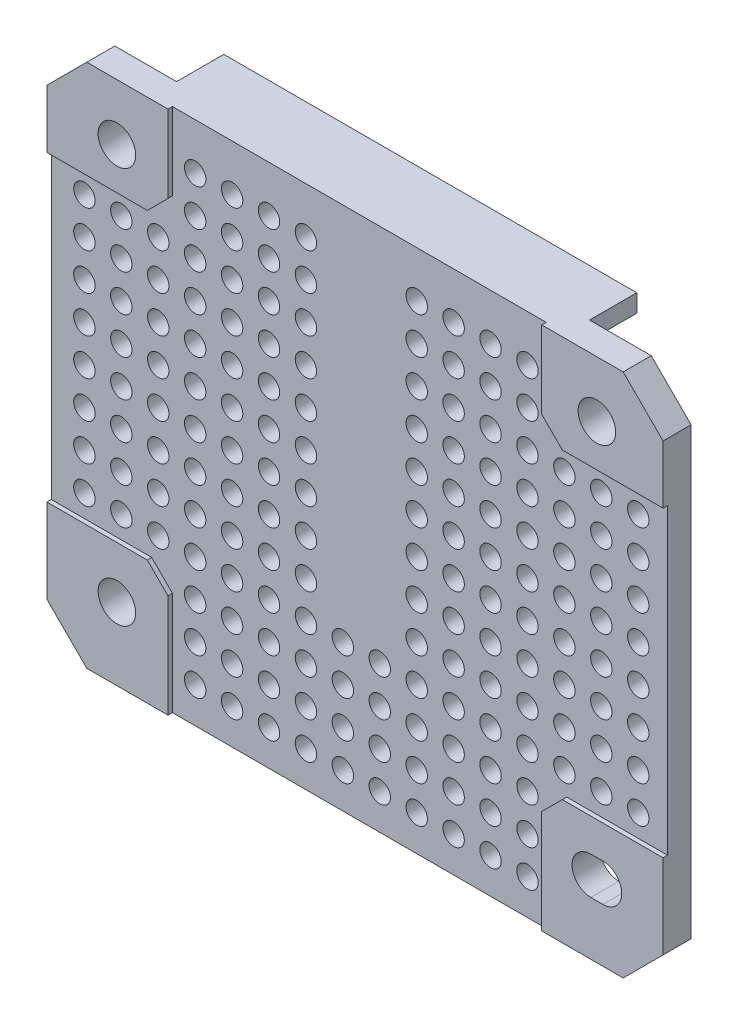
SolidWorks part; units mm, degrees
ref_plane "Front Plane" through (0, 0, 0) normal (0, 0, 1) x (1, 0, 0)
ref_plane "Top Plane" through (0, 0, 0) normal (0, 1, 0) x (1, 0, 0)
ref_plane "Right Plane" through (0, 0, 0) normal (1, 0, 0) x (0, 0, -1)
sketch "Sketch1" plane through (0, 0, 0) normal (0, 0, 1) x (1, 0, 0)
  line L0 (0, 41.7068) -> (3.429, 45.1358)
  line L1 (3.429, 0) -> (49.5554, 0)
  line L2 (0, 3.429) -> (0, 41.7068)
  line L3 (3.429, 45.1358) -> (49.5554, 45.1358)
  line L4 (52.9844, 3.429) -> (52.9844, 41.7068)
  line L5 (49.5554, 45.1358) -> (52.9844, 41.7068)
  line L6 (49.5554, 0) -> (52.9844, 3.429)
  line L7 (0, 3.429) -> (3.429, 0)
  point P0 (0, 0)
  point P1 (52.9844, 45.1358)
  point P2 (0, 45.1358)
  point P3 (52.9844, 0)
  dimension "D1" = 3.429
  dimension "D2" = 45
  dimension "D3" = 3.429
  dimension "D4" = 45
  dimension "D5" = 3.429
  dimension "D6" = 45
  dimension "D7" = 3.429
  dimension "D8" = 45
  dimension "D9" = 52.9844
  dimension "D10" = 45.1358
extrude "Boss-Extrude1" add sketch "Sketch1" along normal blind 2.032
sketch "Sketch2" plane through (0, 0, 2.032) normal (0, 0, 1) x (1, 0, 0)
  line L0 (3.429, 45.1358) -> (0, 41.7068)
  line L1 (0, 41.7068) -> (0, 36.703)
  line L2 (0, 41.7068) -> (0, 3.429) construction
  line L3 (0, 36.703) -> (8.636, 36.703)
  line L4 (10.414, 38.481) -> (10.414, 45.1358)
  line L5 (49.5554, 45.1358) -> (3.429, 45.1358) construction
  line L6 (42.545, 45.1358) -> (42.545, 38.481)
  line L7 (44.323, 36.703) -> (52.9844, 36.703)
  line L8 (52.9844, 3.429) -> (52.9844, 41.7068) construction
  line L9 (42.545, 45.1358) -> (49.5554, 45.1358)
  line L10 (49.5554, 45.1358) -> (52.9844, 41.7068)
  line L11 (52.9844, 41.7068) -> (52.9844, 36.703)
  line L12 (3.429, 45.1358) -> (10.414, 45.1358)
  line L13 (0, 10.668) -> (8.636, 10.668)
  line L14 (10.414, 8.89) -> (10.414, 0)
  line L15 (3.429, 0) -> (49.5554, 0) construction
  line L16 (10.414, 0) -> (3.429, 0)
  line L17 (3.429, 0) -> (0, 3.429)
  line L18 (0, 3.429) -> (0, 10.668)
  line L19 (52.9844, 10.668) -> (44.323, 10.668)
  line L20 (42.545, 8.89) -> (42.545, 0)
  line L21 (42.545, 0) -> (49.5554, 0)
  line L22 (49.5554, 0) -> (52.9844, 3.429)
  line L23 (52.9844, 3.429) -> (52.9844, 10.668)
  line L24 (8.636, 36.703) -> (10.414, 38.481)
  line L25 (42.545, 38.481) -> (44.323, 36.703)
  line L26 (44.323, 10.668) -> (42.545, 8.89)
  line L27 (8.636, 10.668) -> (10.414, 8.89)
  point P8 (10.414, 36.703)
  point P12 (42.545, 36.703)
  point P21 (10.414, 10.668)
  point P30 (42.545, 10.668)
  dimension "D1" = 1.778
  dimension "D2" = 45
  dimension "D3" = 1.778
  dimension "D4" = 45
  dimension "D5" = 1.778
  dimension "D6" = 45
  dimension "D7" = 1.778
  dimension "D8" = 45
  dimension "D9" = 10.668
  dimension "D10" = 10.414
  dimension "D11" = 32.131
  dimension "D12" = 26.035
extrude "Boss-Extrude2" add sketch "Sketch2" along direction (0, 0, -1) on the side of the normal blind 0.381
sketch "Sketch3" plane through (0, 0, 0) normal (0, 0, -1) x (-1, 0, 0)
  line L0 (-49.5554, 45.1358) -> (-3.429, 45.1358) construction
  line L1 (-44.2468, 45.1358) -> (-8.7376, 45.1358)
  line L2 (-44.2468, 45.1358) -> (-44.2468, 43.6118)
  line L3 (-44.2468, 43.6118) -> (-8.7376, 43.6118)
  line L4 (-8.7376, 45.1358) -> (-8.7376, 43.6118)
  line L5 (-52.9844, 3.429) -> (-52.9844, 41.7068) construction
  line L6 (0, 41.7068) -> (0, 3.429) construction
  dimension "D1" = 8.7376
  dimension "D2" = 8.7376
  dimension "D3" = 1.524
extrude "Boss-Extrude3" add sketch "Sketch3" along normal blind 4.064
sketch "Sketch4" plane through (0, 0, 0) normal (0, 0, -1) x (-1, 0, 0)
  line L0 (-47.8155, 6.223) -> (-46.7741, 6.223) construction
  line L1 (-47.8155, 7.8359) -> (-46.7741, 7.8359)
  line L2 (-47.8155, 4.6101) -> (-46.7741, 4.6101)
  line L3 (-45.1612, 6.223) -> (-45.1612, 8.2594) construction
  line L4 (-49.4284, 6.223) -> (-49.4284, 8.2594) construction
  line L5 (0, 41.7068) -> (0, 3.429) construction
  line L6 (-3.429, 0) -> (-49.5554, 0) construction
  circle A0 centre (-47.2948, 40.3098) radius 1.6129
  circle A1 centre (-6.0198, 40.3098) radius 1.6129
  circle A2 centre (-6.0198, 6.223) radius 1.6129
  arc A3 (-47.8155, 7.8359) -> (-47.8155, 4.6101) centre (-47.8155, 6.223) ccw
  arc A4 (-46.7741, 4.6101) -> (-46.7741, 7.8359) centre (-46.7741, 6.223) ccw
  circle A5 centre (-2.8448, 12.573) radius 0.9207
  circle A6 centre (-6.0198, 12.573) radius 0.9208
  circle A7 centre (-9.1948, 12.573) radius 0.9208
  circle A12 centre (-25.0698, 12.573) radius 0.9208 [skipped]
  circle A13 centre (-28.2448, 12.573) radius 0.9208 [skipped]
  circle A17 centre (-40.9448, 12.573) radius 0.9208
  circle A18 centre (-44.1198, 12.573) radius 0.9208
  circle A19 centre (-47.2948, 12.573) radius 0.9208
  circle A20 centre (-50.4698, 12.573) radius 0.9208
  circle A21 centre (-6.0198, 15.748) radius 0.9208
  circle A22 centre (-9.1948, 15.748) radius 0.9208
  circle A23 centre (-12.3698, 15.748) radius 0.9208
  circle A24 centre (-15.5448, 15.748) radius 0.9208
  circle A25 centre (-18.7198, 15.748) radius 0.9208
  circle A26 centre (-21.8948, 15.748) radius 0.9208
  circle A27 centre (-25.0698, 15.748) radius 0.9208 [skipped]
  circle A28 centre (-28.2448, 15.748) radius 0.9208 [skipped]
  circle A29 centre (-31.4198, 15.748) radius 0.9208
  circle A30 centre (-34.5948, 15.748) radius 0.9208
  circle A31 centre (-37.7698, 15.748) radius 0.9207
  circle A32 centre (-40.9448, 15.748) radius 0.9208
  circle A33 centre (-44.1198, 15.748) radius 0.9208
  circle A34 centre (-47.2948, 15.748) radius 0.9208
  circle A35 centre (-50.4698, 15.748) radius 0.9208
  circle A36 centre (-6.0198, 18.923) radius 0.9208
  circle A37 centre (-9.1948, 18.923) radius 0.9208
  circle A38 centre (-12.3698, 18.923) radius 0.9208
  circle A39 centre (-15.5448, 18.923) radius 0.9208
  circle A40 centre (-18.7198, 18.923) radius 0.9208
  circle A41 centre (-21.8948, 18.923) radius 0.9208
  circle A42 centre (-25.0698, 18.923) radius 0.9208 [skipped]
  circle A43 centre (-28.2448, 18.923) radius 0.9207 [skipped]
  circle A44 centre (-31.4198, 18.923) radius 0.9207
  circle A45 centre (-34.5948, 18.923) radius 0.9208
  circle A46 centre (-37.7698, 18.923) radius 0.9208
  circle A47 centre (-40.9448, 18.923) radius 0.9208
  circle A48 centre (-44.1198, 18.923) radius 0.9207
  circle A49 centre (-47.2948, 18.923) radius 0.9208
  circle A50 centre (-50.4698, 18.923) radius 0.9208
  circle A51 centre (-6.0198, 22.098) radius 0.9208
  circle A52 centre (-9.1948, 22.098) radius 0.9208
  circle A53 centre (-12.3698, 22.098) radius 0.9208
  circle A54 centre (-15.5448, 22.098) radius 0.9207
  circle A55 centre (-18.7198, 22.098) radius 0.9208
  circle A56 centre (-21.8948, 22.098) radius 0.9208
  circle A57 centre (-25.0698, 22.098) radius 0.9208 [skipped]
  circle A58 centre (-28.2448, 22.098) radius 0.9208 [skipped]
  circle A59 centre (-31.4198, 22.098) radius 0.9207
  circle A60 centre (-34.5948, 22.098) radius 0.9208
  circle A61 centre (-37.7698, 22.098) radius 0.9208
  circle A62 centre (-40.9448, 22.098) radius 0.9208
  circle A63 centre (-44.1198, 22.098) radius 0.9208
  circle A64 centre (-47.2948, 22.098) radius 0.9207
  circle A65 centre (-50.4698, 22.098) radius 0.9208
  circle A66 centre (-6.0198, 25.273) radius 0.9207
  circle A67 centre (-9.1948, 25.273) radius 0.9208
  circle A68 centre (-12.3698, 25.273) radius 0.9208
  circle A69 centre (-15.5448, 25.273) radius 0.9208
  circle A70 centre (-18.7198, 25.273) radius 0.9208
  circle A71 centre (-21.8948, 25.273) radius 0.9207
  circle A72 centre (-25.0698, 25.273) radius 0.9207 [skipped]
  circle A73 centre (-28.2448, 25.273) radius 0.9208 [skipped]
  circle A74 centre (-31.4198, 25.273) radius 0.9208
  circle A75 centre (-34.5948, 25.273) radius 0.9208
  circle A76 centre (-37.7698, 25.273) radius 0.9207
  circle A77 centre (-40.9448, 25.273) radius 0.9207
  circle A78 centre (-44.1198, 25.273) radius 0.9208
  circle A79 centre (-47.2948, 25.273) radius 0.9208
  circle A80 centre (-50.4698, 25.273) radius 0.9208
  circle A81 centre (-6.0198, 28.448) radius 0.9208
  circle A82 centre (-9.1948, 28.448) radius 0.9208
  circle A83 centre (-12.3698, 28.448) radius 0.9208
  circle A84 centre (-15.5448, 28.448) radius 0.9208
  circle A85 centre (-18.7198, 28.448) radius 0.9208
  circle A86 centre (-21.8948, 28.448) radius 0.9208
  circle A87 centre (-25.0698, 28.448) radius 0.9208 [skipped]
  circle A88 centre (-28.2448, 28.448) radius 0.9208 [skipped]
  circle A89 centre (-31.4198, 28.448) radius 0.9208
  circle A90 centre (-34.5948, 28.448) radius 0.9208
  circle A91 centre (-37.7698, 28.448) radius 0.9208
  circle A92 centre (-40.9448, 28.448) radius 0.9208
  circle A93 centre (-44.1198, 28.448) radius 0.9208
  circle A94 centre (-47.2948, 28.448) radius 0.9208
  circle A95 centre (-50.4698, 28.448) radius 0.9208
  circle A96 centre (-6.0198, 31.623) radius 0.9208
  circle A97 centre (-9.1948, 31.623) radius 0.9208
  circle A98 centre (-12.3698, 31.623) radius 0.9207
  circle A99 centre (-15.5448, 31.623) radius 0.9208
  circle A100 centre (-18.7198, 31.623) radius 0.9207
  circle A101 centre (-21.8948, 31.623) radius 0.9208
  circle A102 centre (-25.0698, 31.623) radius 0.9208 [skipped]
  circle A103 centre (-28.2448, 31.623) radius 0.9207 [skipped]
  circle A104 centre (-31.4198, 31.623) radius 0.9208
  circle A105 centre (-34.5948, 31.623) radius 0.9207
  circle A106 centre (-37.7698, 31.623) radius 0.9208
  circle A107 centre (-40.9448, 31.623) radius 0.9208
  circle A108 centre (-44.1198, 31.623) radius 0.9207
  circle A109 centre (-47.2948, 31.623) radius 0.9208
  circle A110 centre (-50.4698, 31.623) radius 0.9207
  circle A111 centre (-6.0198, 34.798) radius 0.9208
  circle A112 centre (-9.1948, 34.798) radius 0.9207
  circle A113 centre (-12.3698, 34.798) radius 0.9208
  circle A114 centre (-15.5448, 34.798) radius 0.9208
  circle A115 centre (-18.7198, 34.798) radius 0.9207
  circle A116 centre (-21.8948, 34.798) radius 0.9208
  circle A117 centre (-25.0698, 34.798) radius 0.9207 [skipped]
  circle A118 centre (-28.2448, 34.798) radius 0.9208 [skipped]
  circle A119 centre (-31.4198, 34.798) radius 0.9207
  circle A120 centre (-34.5948, 34.798) radius 0.9207
  circle A121 centre (-37.7698, 34.798) radius 0.9208
  circle A122 centre (-40.9448, 34.798) radius 0.9207
  circle A123 centre (-44.1198, 34.798) radius 0.9208
  circle A124 centre (-47.2948, 34.798) radius 0.9207
  circle A125 centre (-50.4698, 34.798) radius 0.9207
  circle A126 centre (-6.0198, 37.973) radius 0.9207 [skipped]
  circle A127 centre (-9.1948, 37.973) radius 0.9207 [skipped]
  circle A128 centre (-12.3698, 37.973) radius 0.9208
  circle A129 centre (-15.5448, 37.973) radius 0.9207
  circle A130 centre (-18.7198, 37.973) radius 0.9208
  circle A131 centre (-21.8948, 37.973) radius 0.9207
  circle A132 centre (-25.0698, 37.973) radius 0.9207 [skipped]
  circle A133 centre (-28.2448, 37.973) radius 0.9208 [skipped]
  circle A134 centre (-31.4198, 37.973) radius 0.9207
  circle A135 centre (-34.5948, 37.973) radius 0.9208
  circle A136 centre (-37.7698, 37.973) radius 0.9207
  circle A137 centre (-40.9448, 37.973) radius 0.9207
  circle A138 centre (-44.1198, 37.973) radius 0.9208 [skipped]
  circle A139 centre (-47.2948, 37.973) radius 0.9207 [skipped]
  circle A140 centre (-50.4698, 37.973) radius 0.9208 [skipped]
  circle A142 centre (-9.1948, 41.148) radius 0.9208 [skipped]
  circle A143 centre (-12.3698, 41.148) radius 0.9207
  circle A144 centre (-15.5448, 41.148) radius 0.9207
  circle A145 centre (-18.7198, 41.148) radius 0.9208
  circle A146 centre (-21.8948, 41.148) radius 0.9207
  circle A147 centre (-25.0698, 41.148) radius 0.9208 [skipped]
  circle A148 centre (-28.2448, 41.148) radius 0.9207 [skipped]
  circle A149 centre (-31.4198, 41.148) radius 0.9207
  circle A150 centre (-34.5948, 41.148) radius 0.9208
  circle A151 centre (-37.7698, 41.148) radius 0.9207
  circle A152 centre (-40.9448, 41.148) radius 0.9208
  circle A153 centre (-44.1198, 41.148) radius 0.9207 [skipped]
  circle A154 centre (-47.2948, 41.148) radius 0.9208 [skipped]
  circle A155 centre (-50.4698, 41.148) radius 0.9208 [skipped]
  circle A156 centre (-2.8448, 15.748) radius 0.9208
  circle A157 centre (-2.8448, 18.923) radius 0.9208
  circle A158 centre (-2.8448, 22.098) radius 0.9208
  circle A159 centre (-2.8448, 25.273) radius 0.9208
  circle A160 centre (-2.8448, 28.448) radius 0.9208
  circle A161 centre (-2.8448, 31.623) radius 0.9207
  circle A162 centre (-2.8448, 34.798) radius 0.9207
  circle A163 centre (-2.8448, 37.973) radius 0.9208 [skipped]
  circle A164 centre (-2.8448, 41.148) radius 0.9208 [skipped]
  circle A165 centre (-31.4198, 12.573) radius 0.9208 [skipped]
  circle A166 centre (-34.5948, 12.573) radius 0.9208 [skipped]
  circle A167 centre (-37.7698, 12.573) radius 0.9208 [skipped]
  circle A168 centre (-12.3698, 12.573) radius 0.9208 [skipped]
  circle A169 centre (-15.5448, 12.573) radius 0.9208 [skipped]
  circle A170 centre (-18.7198, 12.573) radius 0.9208 [skipped]
  circle A171 centre (-21.8948, 12.573) radius 0.9208 [skipped]
  circle A172 centre (-37.7698, 12.573) radius 0.9208
  circle A173 centre (-34.5948, 12.573) radius 0.9208
  circle A174 centre (-31.4198, 12.573) radius 0.9208
  circle A175 centre (-28.2448, 12.573) radius 0.9208
  circle A176 centre (-25.0698, 12.573) radius 0.9208
  circle A177 centre (-21.8948, 12.573) radius 0.9208
  circle A178 centre (-18.7198, 12.573) radius 0.9208
  circle A179 centre (-15.5448, 12.573) radius 0.9208
  circle A180 centre (-12.3698, 12.573) radius 0.9208
  circle A181 centre (-37.7698, 9.398) radius 0.9208
  circle A182 centre (-34.5948, 9.398) radius 0.9207
  circle A183 centre (-31.4198, 9.398) radius 0.9208
  circle A184 centre (-28.2448, 9.398) radius 0.9208
  circle A185 centre (-25.0698, 9.398) radius 0.9208
  circle A186 centre (-21.8948, 9.398) radius 0.9208
  circle A187 centre (-18.7198, 9.398) radius 0.9208
  circle A188 centre (-15.5448, 9.398) radius 0.9208
  circle A189 centre (-12.3698, 9.398) radius 0.9208
  circle A190 centre (-37.7698, 6.223) radius 0.9208
  circle A191 centre (-34.5948, 6.223) radius 0.9208
  circle A192 centre (-31.4198, 6.223) radius 0.9208
  circle A193 centre (-28.2448, 6.223) radius 0.9208
  circle A194 centre (-25.0698, 6.223) radius 0.9208
  circle A195 centre (-21.8948, 6.223) radius 0.9208
  circle A196 centre (-18.7198, 6.223) radius 0.9208
  circle A197 centre (-15.5448, 6.223) radius 0.9208
  circle A198 centre (-12.3698, 6.223) radius 0.9208
  circle A199 centre (-37.7698, 3.048) radius 0.9208
  circle A200 centre (-34.5948, 3.048) radius 0.9208
  circle A201 centre (-31.4198, 3.048) radius 0.9207
  circle A202 centre (-28.2448, 3.048) radius 0.9208
  circle A203 centre (-25.0698, 3.048) radius 0.9208
  circle A204 centre (-21.8948, 3.048) radius 0.9208
  circle A205 centre (-18.7198, 3.048) radius 0.9208
  circle A206 centre (-15.5448, 3.048) radius 0.9208
  circle A207 centre (-12.3698, 3.048) radius 0.9208
  circle A208 centre (-40.9448, 9.398) radius 0.9208
  circle A209 centre (-40.9448, 6.223) radius 0.9208
  circle A210 centre (-40.9448, 3.048) radius 0.9208
  circle A211 centre (-6.0198, 41.148) radius 0.9207 [skipped]
  point P8 (-47.2948, 6.223)
  dimension "D1" = 3.2258
  dimension "D7" = 1.8415
  dimension "D2" = 4.2672
  dimension "D3" = 34.0868
  dimension "D4" = 41.275
  dimension "D5" = 6.0198
  dimension "D6" = 6.223
  dimension "D8" = 3.175
  dimension "D9" = 6.35
  dimension "D12" = 3.175
  dimension "D13" = 3.175
  dimension "D16" = 3.175
  dimension "D17" = 3.175
  dimension "D10" = 16
  dimension "D11" = 10
  dimension "D14" = 10
  dimension "D15" = 4
extrude "Cut-Extrude1" cut sketch "Sketch4" against normal through all
